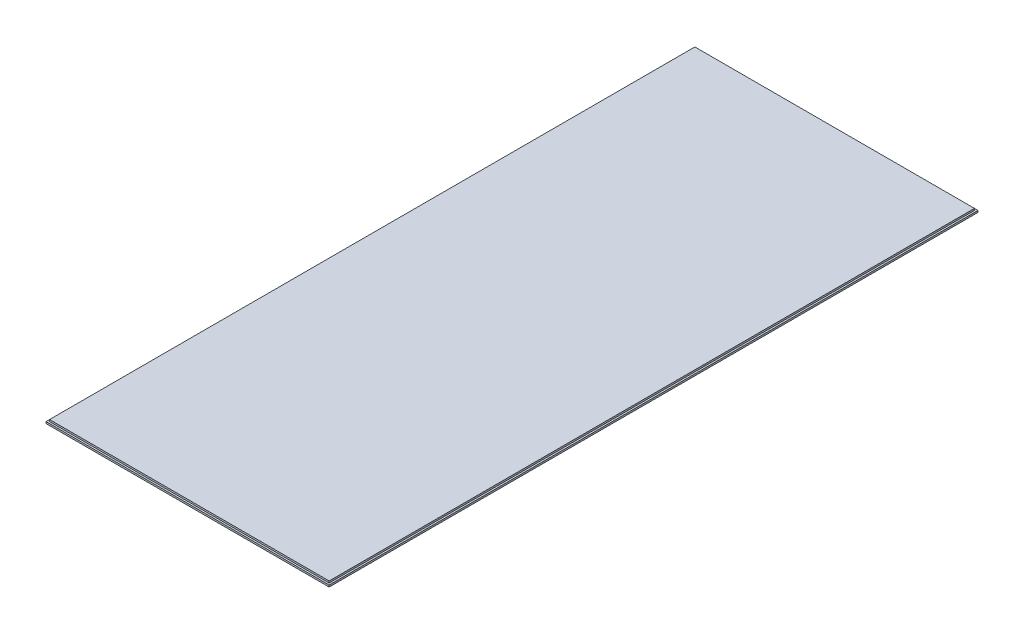
SolidWorks part; units mm, degrees
ref_plane "Front Plane" through (0, 0, 0) normal (0, 0, 1) x (1, 0, 0)
ref_plane "Top Plane" through (0, 0, 0) normal (0, 1, 0) x (1, 0, 0)
ref_plane "Right Plane" through (0, 0, 0) normal (1, 0, 0) x (0, 0, -1)
sketch "Sketch1" plane through (0, 0, 0) normal (0, 1, 0) x (1, 0, 0)
  line L1 (-59.3362, -54.2024) -> (131.1638, -54.2024)
  line L2 (-59.3362, -54.2024) -> (-59.3362, 382.3601)
  line L3 (-59.3362, 382.3601) -> (131.1638, 382.3601)
  line L4 (131.1638, -54.2024) -> (131.1638, 382.3601)
  dimension "D1" = 436.5625
  dimension "D2" = 190.5
extrude "Boss-Extrude1" add sketch "Sketch1" along normal blind 1.1906
sketch "Sketch2" plane through (0, 1.1906, 0) normal (0, 1, 0) x (1, 0, 0)
  line L0 (-59.3362, 382.3601) -> (-59.3362, -54.2024) construction
  line L1 (-58.1456, 381.1695) -> (129.9732, 381.1695)
  line L2 (-58.1456, 381.1695) -> (-58.1456, -53.0117)
  line L3 (-58.1456, -53.0117) -> (129.9732, -53.0117)
  line L4 (129.9732, 381.1695) -> (129.9732, -53.0117)
  line L5 (131.1638, -54.2024) -> (131.1638, 382.3601) construction
  line L6 (131.1638, 382.3601) -> (-59.3362, 382.3601) construction
  line L7 (-59.3362, -54.2024) -> (131.1638, -54.2024) construction
  dimension "D1" = 1.1906
  dimension "D2" = 1.1906
  dimension "D3" = 1.1906
  dimension "D4" = 1.1906
extrude "Boss-Extrude2" add sketch "Sketch2" along normal blind 1.1906
